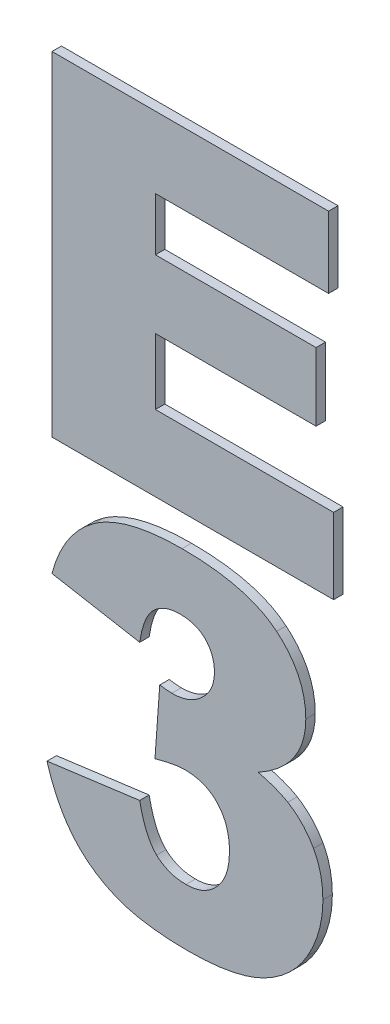
SolidWorks part; units mm, degrees
ref_plane "Alzado" through (0, 0, 0) normal (0, 0, 1) x (1, 0, 0)
ref_plane "Planta" through (0, 0, 0) normal (0, 1, 0) x (1, 0, 0)
ref_plane "Vista lateral" through (0, 0, 0) normal (1, 0, 0) x (0, 0, -1)
sketch "Sketch1" plane through (0, 0, 0) normal (0, 0, 1) x (1, 0, 0)
  line L0 (-144.2111, 752.5076) -> (148.552, 752.5076)
  line L1 (148.552, 752.5076) -> (148.552, 677.0259)
  line L2 (148.552, 677.0259) -> (-34.7264, 677.0259)
  line L3 (-34.7264, 677.0259) -> (-34.7264, 620.8366)
  line L4 (-34.7264, 620.8366) -> (135.2884, 620.8366)
  line L5 (135.2884, 620.8366) -> (135.2884, 548.731)
  line L6 (135.2884, 548.731) -> (-34.7264, 548.731)
  line L7 (-34.7264, 548.731) -> (-34.7264, 479.037)
  line L8 (-34.7264, 479.037) -> (153.8574, 479.037)
  line L9 (153.8574, 479.037) -> (153.8574, 398.9733)
  line L10 (153.8574, 398.9733) -> (-144.2111, 398.9733)
  line L11 (-144.2111, 398.9733) -> (-144.2111, 752.5076)
  line L12 (-51.3662, 257.3132) -> (-144.2111, 273.9529)
  line L13 (-149.5166, 99.3562) -> (-51.3662, 112.3786)
  line L14 (-35.2087, 158.6805) -> (-30.1445, 228.8568)
  spline S0 degree 3 poles (-144.2111, 273.9529) (-136.4942, 303.5347) (-121.7033, 326.2034) (-99.8385, 341.9589) knots 0 0 0 0 1 1 1 1
  spline S1 degree 3 poles (-99.8385, 341.9589) (-77.8129, 357.7144) (-46.7038, 365.5921) (-6.5112, 365.5921) knots 0 0 0 0 1 1 1 1
  spline S2 degree 3 poles (-6.5112, 365.5921) (39.6299, 365.5921) (72.9898, 356.9909) (93.5685, 339.7885) knots 0 0 0 0 1 1 1 1
  spline S3 degree 3 poles (93.5685, 339.7885) (114.1471, 322.586) (124.4364, 300.9624) (124.4364, 274.9176) knots 0 0 0 0 1 1 1 1
  spline S4 degree 3 poles (124.4364, 274.9176) (124.4364, 259.6444) (120.2564, 245.8181) (111.8963, 233.4388) knots 0 0 0 0 1 1 1 1
  spline S5 degree 3 poles (111.8963, 233.4388) (103.5362, 221.0594) (90.9157, 210.2074) (74.0348, 200.8828) knots 0 0 0 0 1 1 1 1
  spline S6 degree 3 poles (74.0348, 200.8828) (87.7003, 197.5066) (98.1504, 193.5677) (105.3851, 189.0661) knots 0 0 0 0 1 1 1 1
  spline S7 degree 3 poles (105.3851, 189.0661) (117.1213, 181.8314) (126.2048, 172.2656) (132.6357, 160.3686) knots 0 0 0 0 1 1 1 1
  spline S8 degree 3 poles (132.6357, 160.3686) (139.2273, 148.6323) (142.5231, 134.5649) (142.5231, 118.1663) knots 0 0 0 0 1 1 1 1
  spline S9 degree 3 poles (142.5231, 118.1663) (142.5231, 97.5877) (137.1373, 77.8129) (126.3656, 58.842) knots 0 0 0 0 1 1 1 1
  spline S10 degree 3 poles (126.3656, 58.842) (115.594, 40.0318) (100.0797, 25.4821) (79.8226, 15.1928) knots 0 0 0 0 1 1 1 1
  spline S11 degree 3 poles (79.8226, 15.1928) (59.5655, 5.0643) (32.9579, 0) (0, 0) knots 0 0 0 0 1 1 1 1
  spline S12 degree 3 poles (0, 0) (-32.1541, 0) (-57.5558, 3.7781) (-76.2052, 11.3343) knots 0 0 0 0 1 1 1 1
  spline S13 degree 3 poles (-76.2052, 11.3343) (-94.6938, 18.8905) (-109.967, 29.9033) (-122.0248, 44.3726) knots 0 0 0 0 1 1 1 1
  spline S14 degree 3 poles (-122.0248, 44.3726) (-133.9218, 59.0028) (-143.0858, 77.3306) (-149.5166, 99.3562) knots 0 0 0 0 1 1 1 1
  spline S15 degree 3 poles (-51.3662, 112.3786) (-47.5077, 92.6038) (-41.5592, 78.8579) (-33.5206, 71.141) knots 0 0 0 0 1 1 1 1
  spline S16 degree 3 poles (-33.5206, 71.141) (-25.3213, 63.5847) (-14.9516, 59.8066) (-2.4116, 59.8066) knots 0 0 0 0 1 1 1 1
  spline S17 degree 3 poles (-2.4116, 59.8066) (10.7716, 59.8066) (21.704, 64.6297) (30.3856, 74.276) knots 0 0 0 0 1 1 1 1
  spline S18 degree 3 poles (30.3856, 74.276) (39.228, 83.9222) (43.6492, 96.7838) (43.6492, 112.8609) knots 0 0 0 0 1 1 1 1
  spline S19 degree 3 poles (43.6492, 112.8609) (43.6492, 129.2595) (39.3888, 141.9604) (30.868, 150.9635) knots 0 0 0 0 1 1 1 1
  spline S20 degree 3 poles (30.868, 150.9635) (22.5079, 159.9666) (11.0932, 164.4682) (-3.3762, 164.4682) knots 0 0 0 0 1 1 1 1
  spline S21 degree 3 poles (-3.3762, 164.4682) (-11.0931, 164.4682) (-21.704, 162.539) (-35.2087, 158.6805) knots 0 0 0 0 1 1 1 1
  spline S22 degree 3 poles (-30.1445, 228.8568) (-24.6783, 228.0529) (-20.4178, 227.651) (-17.3632, 227.651) knots 0 0 0 0 1 1 1 1
  spline S23 degree 3 poles (-17.3632, 227.651) (-4.5015, 227.651) (6.1897, 231.7507) (14.7105, 239.95) knots 0 0 0 0 1 1 1 1
  spline S24 degree 3 poles (14.7105, 239.95) (23.3921, 248.1493) (27.7329, 257.8759) (27.7329, 269.1298) knots 0 0 0 0 1 1 1 1
  spline S25 degree 3 poles (27.7329, 269.1298) (27.7329, 279.9015) (24.5175, 288.5027) (18.0867, 294.9335) knots 0 0 0 0 1 1 1 1
  spline S26 degree 3 poles (18.0867, 294.9335) (11.6559, 301.3643) (2.8135, 304.5797) (-8.4405, 304.5797) knots 0 0 0 0 1 1 1 1
  spline S27 degree 3 poles (-8.4405, 304.5797) (-20.0159, 304.5797) (-29.421, 301.0428) (-36.6557, 293.9689) knots 0 0 0 0 1 1 1 1
  spline S28 degree 3 poles (-36.6557, 293.9689) (-43.8903, 287.0557) (-48.7938, 274.8372) (-51.3662, 257.3132) knots 0 0 0 0 1 1 1 1
extrude "Boss-Extrude1" add sketch "Sketch1" along normal blind 10
